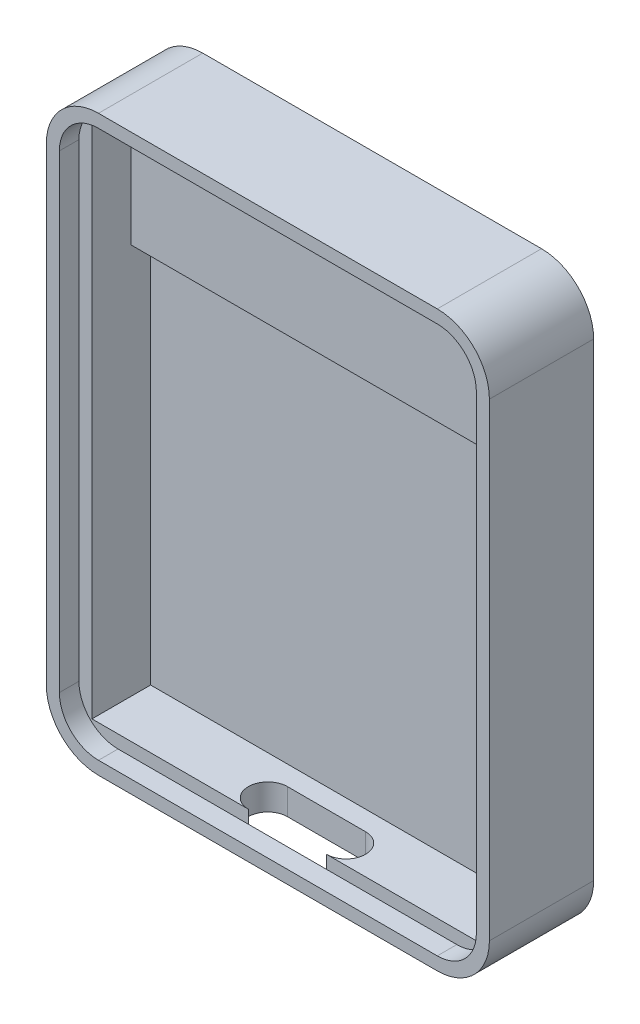
SolidWorks part; units mm, degrees
ref_plane "Спереди" through (0, 0, 0) normal (0, 0, 1) x (1, 0, 0)
ref_plane "Сверху" through (0, 0, 0) normal (0, 1, 0) x (1, 0, 0)
ref_plane "Справа" through (0, 0, 0) normal (1, 0, 0) x (0, 0, -1)
sketch "Эскиз1" plane through (0, 0, 0) normal (0, 0, 1) x (1, 0, 0)
  line L1 (-17, 22) -> (17, 22)
  line L2 (-17, 22) -> (-17, -22)
  line L3 (-17, -22) -> (17, -22)
  line L4 (17, 22) -> (17, -22)
  line L5 (-17, 22) -> (17, -22) construction
  line L6 (-17, -22) -> (17, 22) construction
  point P0 (0, 0)
  dimension "D1" = 34
  dimension "D2" = 44
extrude "Бобышка-Вытянуть1" add sketch "Эскиз1" along normal blind 8
sketch "Эскиз2" plane through (0, 0, 8) normal (0, 0, 1) x (1, 0, 0)
  line L1 (-15, 20) -> (15, 20)
  line L2 (-15, 20) -> (-15, -20)
  line L3 (-15, -20) -> (15, -20)
  line L4 (15, 20) -> (15, -20)
  line L5 (-15, 20) -> (15, -20) construction
  line L6 (-15, -20) -> (15, 20) construction
  point P0 (0, 0)
  dimension "D1" = 40
  dimension "D2" = 30
extrude "Вырез-Вытянуть1" cut sketch "Эскиз2" against normal blind 4.5
sketch "Эскиз3" plane through (0, 0, 3.5) normal (0, 0, 1) x (1, 0, 0)
  line L0 (0, -29.654) -> (0, 34.597) construction
  line L2 (15, 10) -> (-15, 10)
  line L3 (15, 10) -> (15, -20)
  line L4 (15, -20) -> (-15, -20)
  line L5 (-15, 10) -> (-15, -20)
  line L6 (15, 10) -> (-15, -20) construction
  line L7 (15, -20) -> (-15, 10) construction
  point P3 (0, -5)
  dimension "D1" = 30
extrude "Вырез-Вытянуть2" cut sketch "Эскиз3" against normal blind 1.5
fillet "Скругление1" radius 4 4 edges at (17, -22, 4) (17, 22, 4) (-17, 22, 4) (-17, -22, 4)
sketch "Эскиз4" plane through (0, -22, 0) normal (0, -1, 0) x (1, 0, 0)
  line L0 (0, 11.1543) -> (0, -4.5462) construction
  line L1 (-6.2465, 5) -> (6.4318, 5) construction
  line L2 (-13, 0) -> (13, 0) construction
  line L3 (-3, 5) -> (3, 5) construction
  line L4 (-3, 6.5) -> (3, 6.5)
  line L5 (-3, 3.5) -> (3, 3.5)
  arc A0 (-3, 6.5) -> (-3, 3.5) centre (-3, 5) ccw
  arc A1 (3, 3.5) -> (3, 6.5) centre (3, 5) ccw
  point P9 (0, 5)
  dimension "D1" = 5
  dimension "D2" = 3
  dimension "D3" = 3
extrude "Вырез-Вытянуть3" cut sketch "Эскиз4" against normal blind 2
sketch "Эскиз5" plane through (0, 0, 8) normal (0, 0, 1) x (1, 0, 0)
  line L0 (-18.4424, 0) -> (24.1733, 0) construction
  line L1 (-13, -21) -> (13, -21)
  line L2 (0, -24.7805) -> (0, 23.2827) construction
  line L3 (-13, 21) -> (13, 21)
  line L8 (-16, -18) -> (-16, 18)
  line L10 (16, -18) -> (16, 18)
  arc A0 (-13, 21) -> (-16, 18) centre (-13, 18) ccw
  arc A1 (13, 21) -> (16, 18) centre (13, 18) cw
  arc A2 (13, -21) -> (16, -18) centre (13, -18) ccw
  arc A3 (-13, -21) -> (-16, -18) centre (-13, -18) cw
  point P0 (0, 0)
  point P6 (0, 0)
  point P19 (0, 21)
  point P20 (16, 0)
  dimension "D5" = 3
  dimension "D1" = 42
  dimension "D2" = 32
extrude "Вырез-Вытянуть4" cut sketch "Эскиз5" against normal blind 1.5
